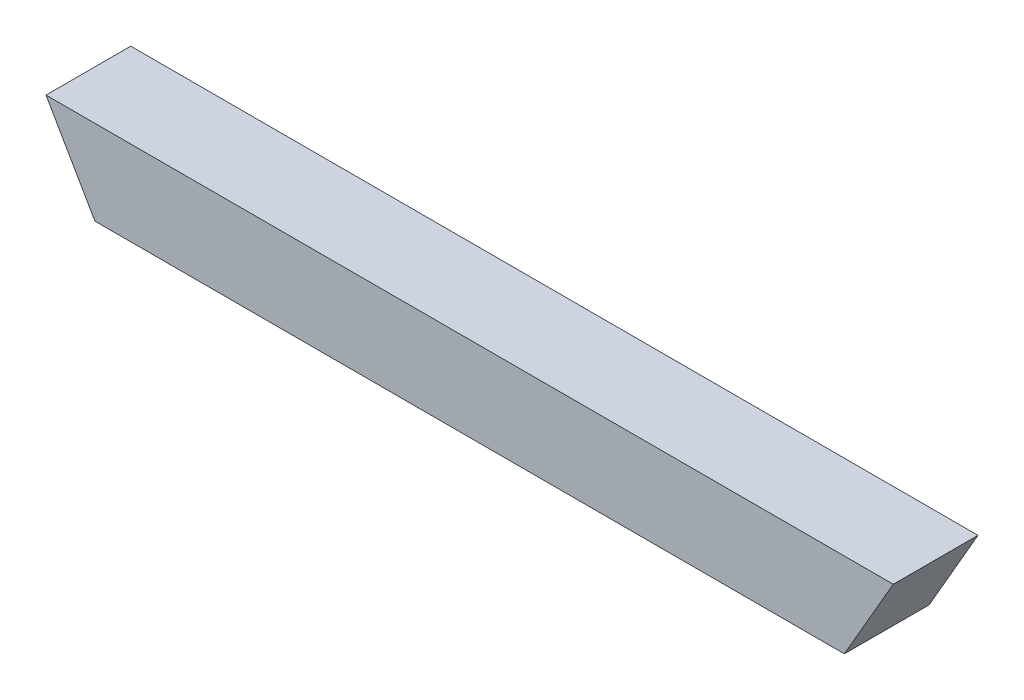
SolidWorks part; units mm, degrees
ref_plane "Front Plane" through (0, 0, 0) normal (0, 0, 1) x (1, 0, 0)
ref_plane "Top Plane" through (0, 0, 0) normal (0, 1, 0) x (1, 0, 0)
ref_plane "Right Plane" through (0, 0, 0) normal (1, 0, 0) x (0, 0, -1)
sketch "Sketch1" plane through (0, 0, 0) normal (0, 0, 1) x (1, 0, 0)
  line L0 (-100, 0) -> (100, 0)
  line L1 (-100, 0) -> (-73.2204, -46.3837) construction
  line L2 (0, 0) -> (0, -20) construction
  line L3 (88.453, -20) -> (-88.453, -20)
  line L4 (-100, 0) -> (-88.453, -20)
  line L5 (88.453, -20) -> (100, 0)
  point P4 (0, 0)
  point P10 (0, -20)
  dimension "D1" = 60
  dimension "D2" = 200
extrude "Boss-Extrude1" add sketch "Sketch1" along normal blind 20
